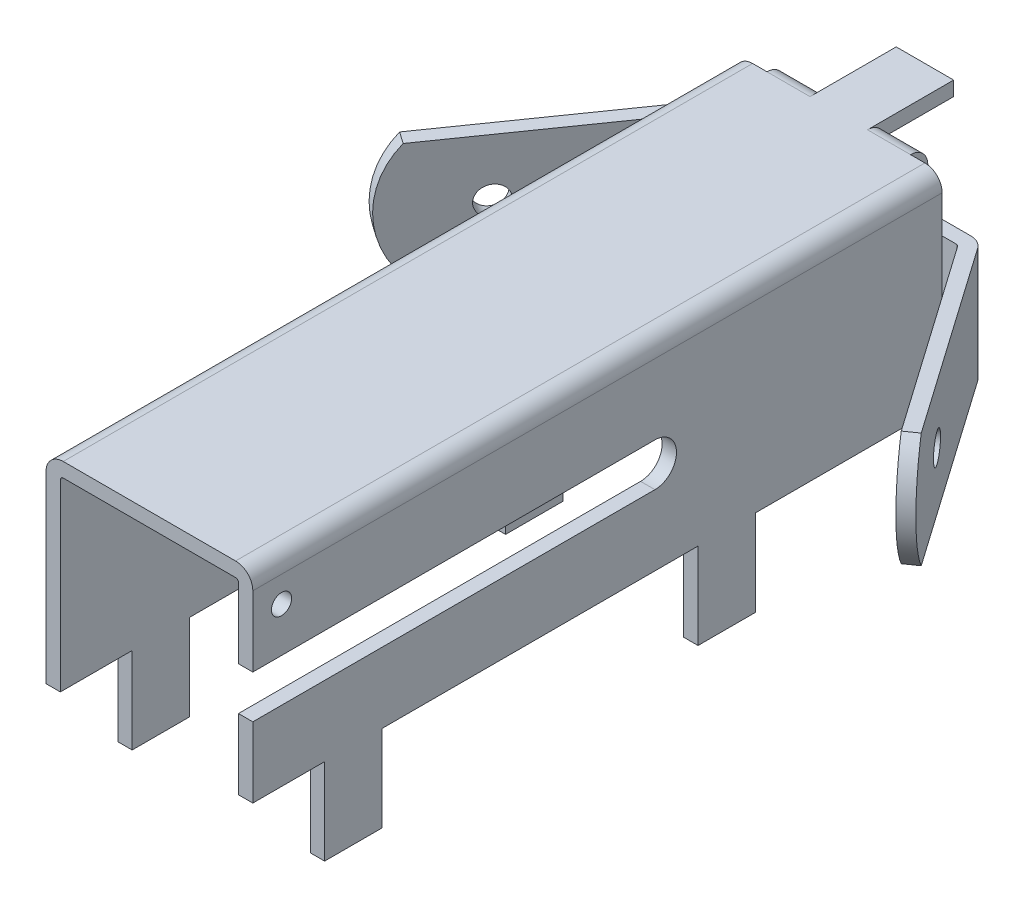
SolidWorks part; units mm, degrees
material "Laiton"
ref_plane "Plan de face" through (0, 0, 0) normal (0, 0, 1) x (1, 0, 0)
ref_plane "Plan de dessus" through (0, 0, 0) normal (0, 1, 0) x (1, 0, 0)
ref_plane "Plan de droite" through (0, 0, 0) normal (1, 0, 0) x (0, 0, -1)
sketch "Esquisse1" plane through (0, 0, 0) normal (0, 0, 1) x (1, 0, 0)
  line L0 (0, 0) -> (0, 7) construction
  line L1 (-3, 7) -> (3, 7)
  line L2 (-3.6, 6.4) -> (-3.6, 0)
  line L3 (-3.1, 0) -> (-3.6, 0)
  line L4 (3.6, 6.4) -> (3.6, 0)
  line L5 (-3, 6.5) -> (3, 6.5)
  line L6 (-3.1, 6.4) -> (-3.1, 0)
  line L7 (3.1, 0) -> (3.6, 0)
  line L8 (3.1, 6.4) -> (3.1, 0)
  arc A0 (3.1, 6.4) -> (3, 6.5) centre (3, 6.4) ccw
  arc A1 (-3.1, 6.4) -> (-3, 6.5) centre (-3, 6.4) cw
  arc A2 (3.6, 6.4) -> (3, 7) centre (3, 6.4) ccw
  arc A3 (-3.6, 6.4) -> (-3, 7) centre (-3, 6.4) cw
  dimension "D6" = 0.6
  dimension "D1" = 7
  dimension "D2" = 7.2
  dimension "D3" = 0.5
extrude "Boss.-Extru.1" add sketch "Esquisse1" along normal blind 24
sketch "Esquisse2" plane through (0, 0, 0) normal (0, 0, -1) x (-1, 0, 0)
  line L0 (-3, 7) -> (3, 7) construction
  line L1 (-1, 7) -> (1, 7)
  line L2 (-1, 7) -> (-1, 6.5)
  line L3 (-1, 6.5) -> (1, 6.5)
  line L4 (1, 7) -> (1, 6.5)
  line L5 (3, 6.5) -> (-3, 6.5) construction
  line L6 (0, 6.5) -> (0, 0) construction
  dimension "D1" = 2
extrude "Boss.-Extru.2" add sketch "Esquisse2" along normal blind 3
sketch "Esquisse5" plane through (-1, 0, 0) normal (-1, 0, 0) x (0, 0, 1)
  line L0 (0, 6.5) -> (0, 7) construction
  line L1 (-0.1, 1) -> (-0.6, 1)
  line L2 (-0.1, 1) -> (-0.1, 6.4)
  line L3 (0, 7) -> (0, 6.5)
  line L4 (-0.6, 1) -> (-0.6, 6.4)
  line L6 (-3, 7) -> (0, 7) construction
  line L7 (-3, 6.5) -> (0, 6.5) construction
  line L8 (24, 6.4) -> (0, 6.4) construction
  arc A0 (0, 6.5) -> (-0.1, 6.4) centre (0, 6.4) ccw
  arc A1 (0, 7) -> (-0.6, 6.4) centre (0, 6.4) ccw
  dimension "D1" = 1
extrude "Boss.-Extru.3" add sketch "Esquisse5" along normal blind 3
sketch "Esquisse6" plane through (-4, 0, 0) normal (-1, 0, 0) x (0, 0, 1)
  line L0 (-0.6, 1) -> (-0.1, 1) construction
  line L1 (-0.6, 7) -> (0, 7)
  line L2 (-0.6, 7) -> (-0.6, 5)
  line L3 (-0.6, 5) -> (0, 5)
  line L4 (0, 7) -> (0, 5)
  line L5 (-0.6, 6.4) -> (-0.6, 1) construction
  line L6 (0, 6.5) -> (0, 7) construction
  arc A0 (0, 7) -> (-0.6, 6.4) centre (0, 6.4) ccw construction
  dimension "D1" = 4
extrude "Enlèv. mat.-Extru.1" cut sketch "Esquisse6" against normal blind 1.5
sketch "Esquisse3" plane through (0, 5, 0) normal (0, 1, 0) x (1, 0, 0)
  line L0 (-4.4915, 0.3441) -> (-9.6537, -7.0282)
  line L1 (-9.6537, -7.0282) -> (-9.2441, -7.315)
  line L2 (-9.2441, -7.315) -> (-4.0819, 0.0574)
  line L3 (-2.5, 0.6) -> (-4, 0.6) construction
  line L4 (-4, 0.6) -> (-4, 0.1) construction
  line L5 (-2.5, 0.1) -> (-4, 0.1) construction
  line L6 (-4, 0.6) -> (-4, 0.1)
  line L7 (0, -3.85) -> (0, 3.85) construction
  arc A0 (-4, 0.6) -> (-4.4915, 0.3441) centre (-4, 0) ccw
  arc A1 (-4, 0.1) -> (-4.0819, 0.0574) centre (-4, 0) ccw
  dimension "D3" = 0.6
  dimension "D1" = 35
  dimension "D2" = 9
extrude "Boss.-Extru.4" add sketch "Esquisse3" against normal up to surface (4 mm away) up to face at (-2.5, 1, -0.35)
sketch "Esquisse8" plane through (-3.1755, 0, -2.2235) normal (-0.8192, 0, -0.5736) x (-0.5736, 0, 0.8192)
  line L0 (11.2943, 1) -> (2.2943, 1) construction
  line L1 (11.2943, 1) -> (11.2943, 5) construction
  line L2 (2.2943, 5) -> (11.2943, 5) construction
  line L3 (11.2943, 1) -> (10.2943, 1)
  line L4 (11.2943, 1) -> (11.2943, 5)
  line L5 (10.2943, 5) -> (11.2943, 5)
  arc A0 (10.2943, 1) -> (10.2943, 5) centre (8.0582, 3) ccw
  circle A1 centre (8.0582, 3) radius 0.5
  dimension "D1" = 3
  dimension "D3" = 1
  dimension "D2" = 1
extrude "Enlèv. mat.-Extru.3" cut sketch "Esquisse8" against normal up to next
sketch "Esquisse9" plane through (0, 0, 0) normal (0, -1, 0) x (1, 0, 0)
  line L0 (-3.6, 24) -> (-3.6, 0) construction
  line L1 (-3.6, 6.5) -> (-3.1, 6.5)
  line L2 (-3.6, 6.5) -> (-3.6, 8.5)
  line L3 (-3.6, 8.5) -> (-3.1, 8.5)
  line L4 (-3.1, 6.5) -> (-3.1, 8.5)
  line L5 (-3.1, 24) -> (-3.1, 0) construction
  line L6 (-3.6, 24) -> (-3.1, 24) construction
  line L7 (-3.6, 19.5) -> (-3.1, 19.5)
  line L8 (-3.6, 19.5) -> (-3.6, 21.5)
  line L9 (-3.6, 21.5) -> (-3.1, 21.5)
  line L10 (-3.1, 19.5) -> (-3.1, 21.5)
  line L11 (-3.6, 21.5) -> (-3.1, 19.5) construction
  circle A0 centre (-3.35, 20.5) radius 1 construction
  point P12 (-3.6, 20.5)
  dimension "D4" = 2
  dimension "D1" = 2
  dimension "D2" = 3.5
  dimension "D3" = 13
extrude "Boss.-Extru.5" add sketch "Esquisse9" along normal blind 3
mirror "Symétrie1" about plane through (0, 0, 0) normal (1, 0, 0) of "Boss.-Extru.5", "Boss.-Extru.3", "Enlèv. mat.-Extru.1", "Boss.-Extru.4", "Enlèv. mat.-Extru.3"
sketch "Esquisse7" plane through (3.6, 0, 0) normal (1, 0, 0) x (0, 0, -1)
  line L0 (-24, 0) -> (-24, 6.4) construction
  line L1 (-24, 3.95) -> (-10, 3.95)
  line L2 (-24, 3.95) -> (-24, 2.45)
  line L3 (-24, 2.45) -> (-10, 2.45)
  line L4 (-24, 6.4) -> (-24, 0) construction
  line L5 (-24, 7) -> (0, 7) construction
  arc A0 (-10, 2.45) -> (-10, 3.95) centre (-10, 3.2) ccw
  circle A1 centre (-23, 5.5) radius 0.35
  point P9 (-24, 3.2)
  dimension "D3" = 0.7
  dimension "D4" = 1
  dimension "D5" = 1.5
  dimension "D1" = 14
  dimension "D2" = 1.5
extrude "Enlèv. mat.-Extru.2" cut sketch "Esquisse7" against normal up to next
